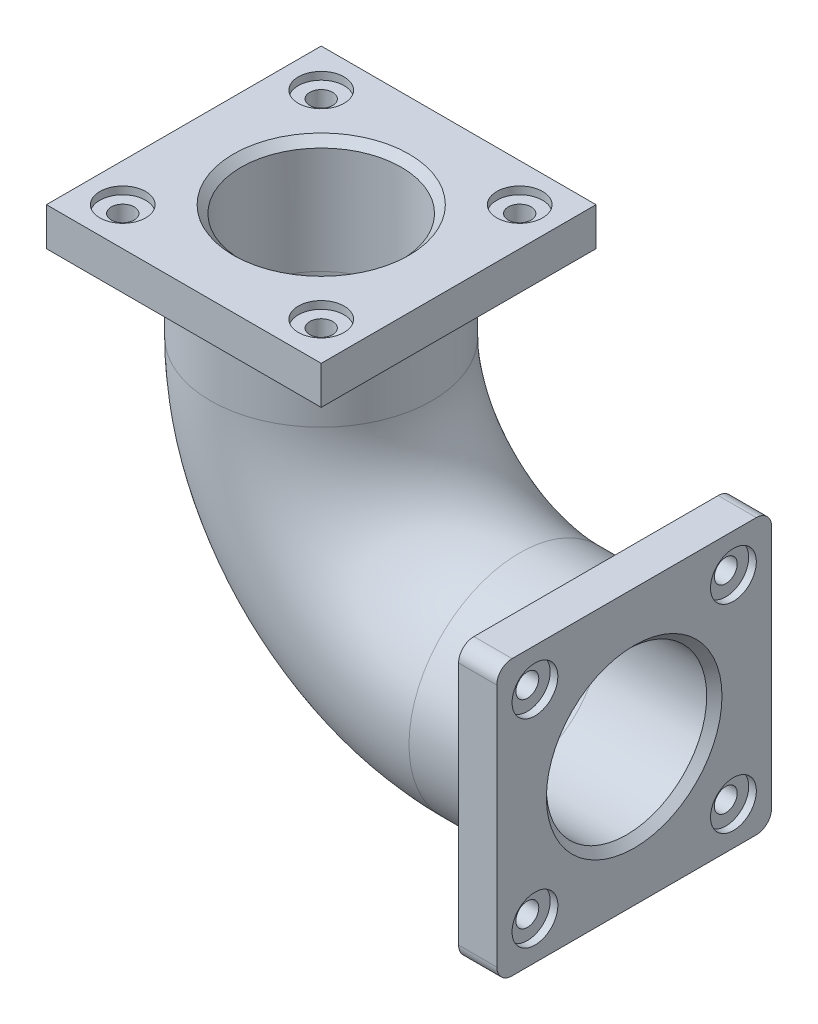
SolidWorks part; units mm, degrees
ref_plane "Front Plane" through (0, 0, 0) normal (0, 0, 1) x (1, 0, 0)
ref_plane "Top Plane" through (0, 0, 0) normal (0, 1, 0) x (1, 0, 0)
ref_plane "Right Plane" through (0, 0, 0) normal (1, 0, 0) x (0, 0, -1)
sketch "Sketch1" plane through (0, 0, 0) normal (0, 0, 1) x (1, 0, 0)
  line L0 (0, 0) -> (-150, 0)
  line L1 (-410, 260) -> (-410, 410)
  arc A0 (-150, 0) -> (-410, 260) centre (-150, 260) cw
  dimension "D2" = 260
  dimension "D1" = 150
sketch "Sketch2" plane through (0, 0, 0) normal (1, 0, 0) x (0, 0, -1)
  circle A0 centre (0, 0) radius 145
sweep "Sweep-Thin1" add profiles "Sketch2" path "Sketch1" parameters "D1"=40
sketch "Sketch4" plane through (0, 0, 0) normal (1, 0, 0) x (0, 0, -1)
  line L1 (-180, 180) -> (180, 180)
  line L2 (-180, 180) -> (-180, -180)
  line L3 (-180, -180) -> (180, -180)
  line L4 (180, 180) -> (180, -180)
  line L5 (-180, 180) -> (180, -180) construction
  line L6 (-180, -180) -> (180, 180) construction
  circle A0 centre (0, 0) radius 145
  point P0 (0, 0)
  dimension "D3" = 290
  dimension "D1" = 360
  dimension "D2" = 360
extrude "Boss-Extrude1" add sketch "Sketch4" against normal blind 50
sketch "Sketch5" plane through (0, 0, 0) normal (1, 0, 0) x (0, 0, -1)
  line L1 (-130, 130) -> (130, 130)
  line L2 (-130, 130) -> (-130, -130)
  line L3 (-130, -130) -> (130, -130)
  line L4 (130, 130) -> (130, -130)
  line L5 (-130, 130) -> (130, -130) construction
  line L6 (-130, -130) -> (130, 130) construction
  circle A0 centre (-130, 130) radius 30
  point P0 (0, 0)
  dimension "D3" = 60
  dimension "D1" = 260
  dimension "D2" = 260
extrude "Cut-Extrude1" cut sketch "Sketch5" against normal blind 10 contours L2 A0 L1 | L1 A0 L2
sketch "Sketch6" plane through (-10, 0, 0) normal (1, 0, 0) x (0, 0, -1)
  circle A0 centre (-130, 130) radius 15
  dimension "D1" = 30
extrude "Cut-Extrude2" cut sketch "Sketch6" against normal up to next
pattern_circular "CirPattern1" count 4 over 360 about axis through (0, 0, 0) along (1, 0, 0) of "Cut-Extrude2", "Cut-Extrude1"
fillet "Fillet1" radius 20 4 edges at (-25, 180, -180) (-25, -180, 180) (-25, -180, -180) (-25, 180, 180)
fillet "Fillet2" radius 10 1 edges at (-50, 0, -145)
chamfer "Chamfer1" distance 10 angle 45 1 edges at (0, 0, -105)
sketch "Sketch7" plane through (0, 410, 0) normal (0, 1, 0) x (1, 0, 0)
  line L1 (-590, 180) -> (-230, 180)
  line L2 (-590, 180) -> (-590, -180)
  line L3 (-590, -180) -> (-230, -180)
  line L4 (-230, 180) -> (-230, -180)
  line L5 (-590, 180) -> (-230, -180) construction
  line L6 (-590, -180) -> (-230, 180) construction
  point P0 (-410, 0)
  circle M4 centre (-410, 0) radius 145
  dimension "D1" = 360
  dimension "D2" = 360
extrude "Boss-Extrude2" add sketch "Sketch7" against normal blind 50 contours L4 L1 L2 L3 M4
sketch "Sketch8" plane through (0, 410, 0) normal (0, 1, 0) x (1, 0, 0)
  line L1 (-540, 130) -> (-280, 130)
  line L2 (-540, 130) -> (-540, -130)
  line L3 (-540, -130) -> (-280, -130)
  line L4 (-280, 130) -> (-280, -130)
  line L5 (-540, 130) -> (-280, -130) construction
  line L6 (-540, -130) -> (-280, 130) construction
  circle A0 centre (-540, 130) radius 30
  point P0 (-410, 0)
  dimension "D3" = 60
  dimension "D1" = 260
  dimension "D2" = 260
extrude "Cut-Extrude3" cut sketch "Sketch8" against normal blind 10 contours L1 A0 L2 | L2 A0 L1
sketch "Sketch9" plane through (0, 400, 0) normal (0, 1, 0) x (1, 0, 0)
  circle A0 centre (-540, 130) radius 15
extrude "Cut-Extrude4" cut sketch "Sketch9" against normal up to next
pattern_circular "CirPattern3" count 4 over 360 about axis through (-410, 0, 0) along (0, 1, 0) of "Cut-Extrude4", "Cut-Extrude3"
chamfer "Chamfer2" distance 10 angle 45 1 edges at (-410, 410, -105)
fillet "Fillet4" radius 10 1 edges at (-410, 360, 145)
